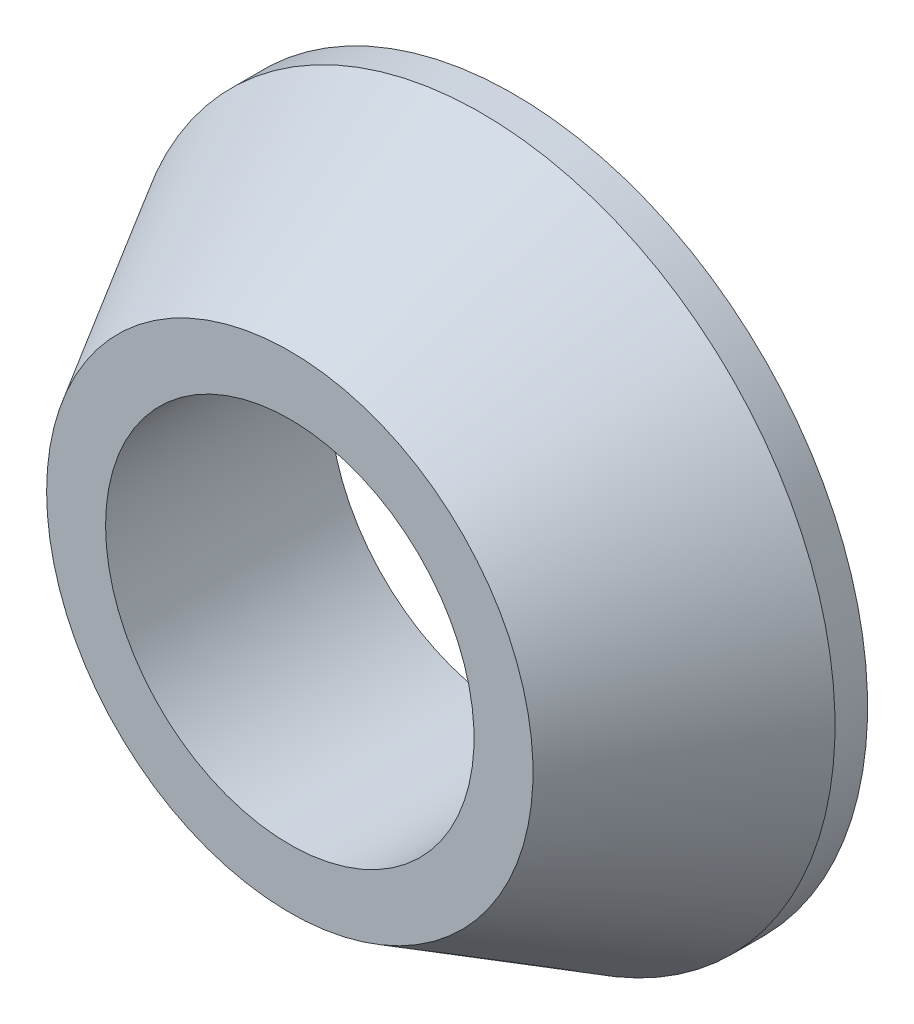
SolidWorks part; units mm, degrees
material "6061-T6 (SS)"
ref_plane "Front Plane" through (0, 0, 0) normal (1, 0, 0) x (0, 1, 0)
ref_plane "Top Plane" through (0, 0, 0) normal (0, 0, 1) x (0, 1, 0)
ref_plane "Right Plane" through (0, 0, 0) normal (0, 1, 0) x (-1, 0, 0)
sketch "Sketch1" plane through (0, 0, 0) normal (1, 0, 0) x (0, 1, 0)
  line L0 (0, 0) -> (0, 4.826) construction
  line L1 (3.9688, 4.826) -> (3.9688, 0)
  line L2 (3.9688, 0) -> (7.62, 0)
  line L3 (7.62, 0) -> (7.62, 0.7016)
  line L4 (7.62, 0.7016) -> (5.2388, 4.826)
  line L5 (5.2388, 4.826) -> (3.9688, 4.826)
  point P5 (6.8282, 1.3398)
  point P9 (5.1169, 4.826)
  dimension "D1" = 4.826
  dimension "D2" = 7.9375
  dimension "D3" = 1.27
  dimension "D4" = 15.24
  dimension "D5" = 30
revolve "Revolve1" add sketch "Sketch1" angle 360 about L0
